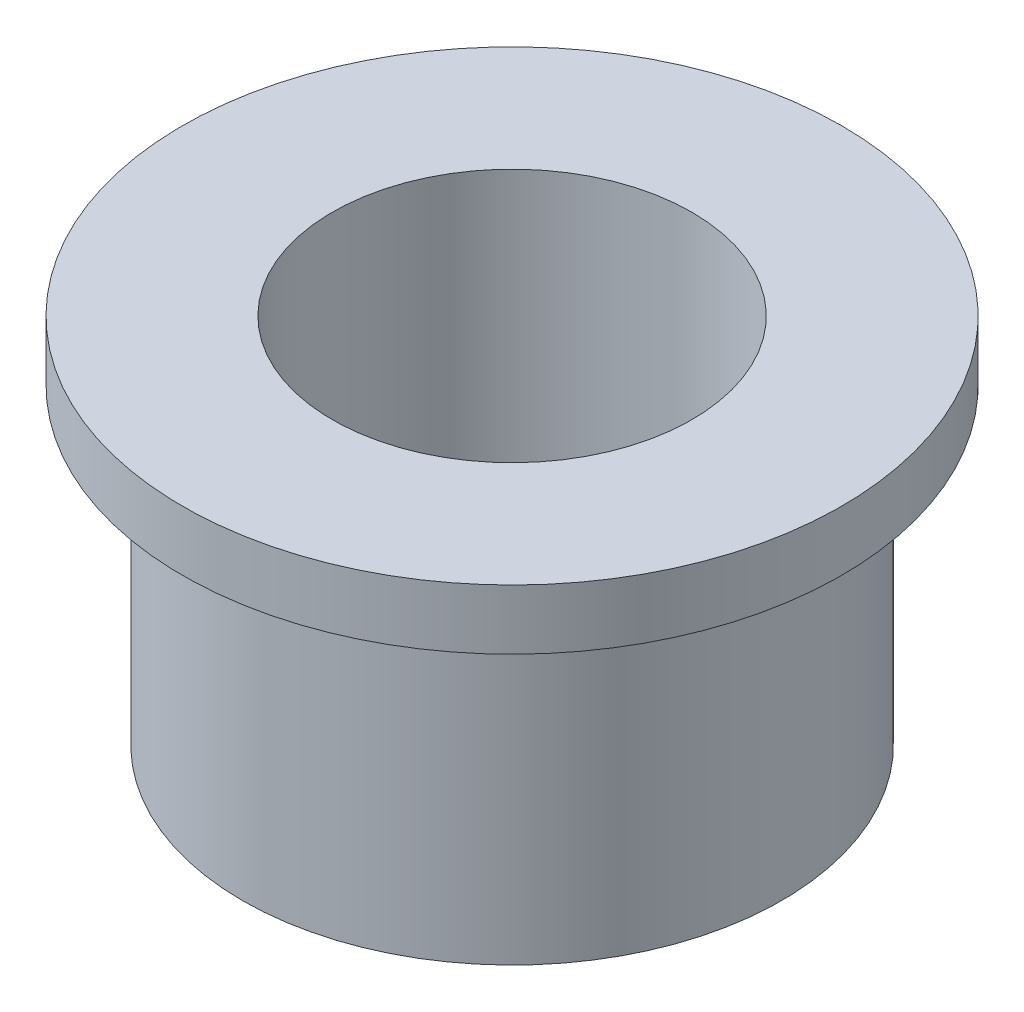
SolidWorks part; units mm, degrees
ref_plane "Płaszczyzna przednia" through (0, 0, 0) normal (0, 0, 1) x (1, 0, 0)
ref_plane "Płaszczyzna górna" through (0, 0, 0) normal (0, 1, 0) x (1, 0, 0)
ref_plane "Płaszczyzna prawa" through (0, 0, 0) normal (1, 0, 0) x (0, 0, -1)
sketch "Szkic1" plane through (0, 0, 0) normal (0, 0, 1) x (1, 0, 0)
  line L0 (0, 0) -> (0, 31) construction
  line L1 (-15, 0) -> (-22.5, 0)
  line L2 (-22.5, 0) -> (-22.5, 26)
  line L4 (-15, 31) -> (-15, 0)
  line L5 (-15, 31) -> (-27.5, 31)
  line L6 (-27.5, 31) -> (-27.5, 26)
  line L7 (-27.5, 26) -> (-22.5, 26)
  dimension "D1" = 22.5
  dimension "D2" = 26
  dimension "D3" = 15
  dimension "D4" = 27.5
revolve "Obrót1" add sketch "Szkic1" angle 360 about L0
